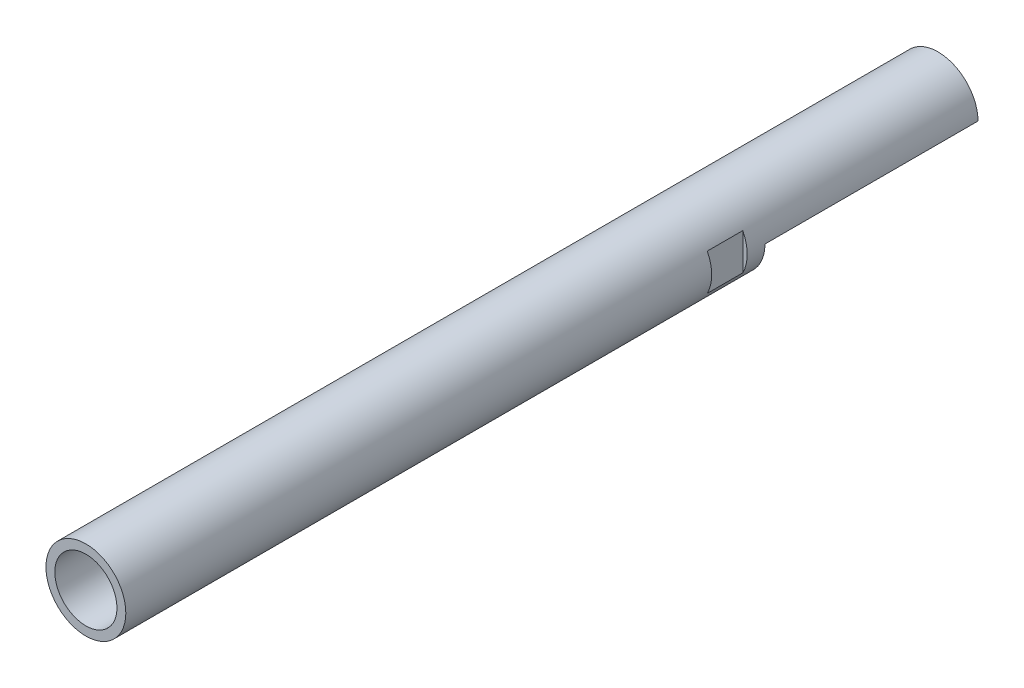
SolidWorks part; units mm, degrees
ref_plane "Front" through (0, 0, 0) normal (0, 0, 1) x (1, 0, 0)
ref_plane "Top" through (0, 0, 0) normal (0, 1, 0) x (1, 0, 0)
ref_plane "Right" through (0, 0, 0) normal (1, 0, 0) x (0, 0, -1)
sketch "Sketch1" plane through (0, 0, 0) normal (0, 0, 1) x (1, 0, 0)
  circle A0 centre (0, 0) radius 9.525
  circle A1 centre (0, 0) radius 14.2875
  dimension "D1" = 19.05
  dimension "D2" = 28.575
extrude "Boss-Extrude1" add sketch "Sketch1" along normal blind 304.8
sketch "Sketch2" plane through (0, 0, 304.8) normal (0, 0, 1) x (1, 0, 0)
  circle A0 centre (0, 0) radius 11.1125
  dimension "D1" = 22.225
extrude "Cut-Extrude1" cut sketch "Sketch2" against normal blind 19.05
sketch "Sketch6" plane through (0, 0, 0) normal (0, 0, -1) x (-1, 0, 0)
  line L0 (14.2875, 0) -> (-14.2875, 0)
  circle A0 centre (0, 0) radius 14.2875 construction
  circle A2 centre (0, 0) radius 14.2875
  arc A3 (-14.2875, 0) -> (14.2875, 0) centre (0, 0) ccw
  dimension "D1" = 0
extrude "Cut-Extrude4" cut sketch "Sketch6" against normal blind 76.2
ref_plane "Plane1" through (0, 0, 82.55) normal (0, 0, -1) x (-1, 0, 0)
sketch "Sketch8" plane through (0, 0, 82.55) normal (0, 0, -1) x (-1, 0, 0)
  line L1 (12.7, 12.7) -> (-12.7, 12.7)
  line L2 (12.7, 12.7) -> (12.7, -12.7)
  line L3 (12.7, -12.7) -> (-12.7, -12.7)
  line L4 (-12.7, 12.7) -> (-12.7, -12.7)
  line L5 (12.7, 12.7) -> (-12.7, -12.7) construction
  line L6 (12.7, -12.7) -> (-12.7, 12.7) construction
  circle A1 centre (0, 0) radius 14.2875
  circle A2 centre (0, 0) radius 14.2875
  dimension "D2" = 25.4
  dimension "D1" = 0
extrude "Cut-Extrude7" cut sketch "Sketch8" against normal blind 12.7 contours L3 A2 | L4 A2
sketch "Sketch9" plane through (0, -12.7, 0) normal (0, -1, 0) x (1, 0, 0)
  line L0 (0, 95.25) -> (0, 304.8) construction
  line L1 (-6.5454, 95.25) -> (6.5454, 95.25) construction
  line L2 (14.2875, 304.8) -> (-14.2875, 304.8) construction
  line L3 (-6.5454, 95.25) -> (6.5454, 95.25) construction
  circle A0 centre (0, 107.95) radius 3.175
  circle A1 centre (0, 158.75) radius 3.175
  dimension "D1" = 63.5
  dimension "D2" = 12.7
  dimension "D3" = 6.35
extrude "Cut-Extrude8" cut sketch "Sketch9" against normal up to next and the other way up to next contours A1 L0 | L0 A1
sketch "Sketch10" plane through (0, 0, 0) normal (0, 0, -1) x (-1, 0, 0)
  line L2 (-14.2875, 0) -> (-9.525, 0)
  line L3 (9.525, 0) -> (14.2875, 0)
  line L4 (-14.2875, 0) -> (-9.525, 0)
  line L5 (9.525, 0) -> (14.2875, 0)
  arc A2 (14.2875, 0) -> (-14.2875, 0) centre (0, 0) ccw
  arc A3 (9.525, 0) -> (-9.525, 0) centre (0, 0) ccw
  arc A4 (14.2875, 0) -> (-14.2875, 0) centre (0, 0) ccw
  arc A5 (9.525, 0) -> (-9.525, 0) centre (0, 0) ccw
  dimension "D1" = 0
